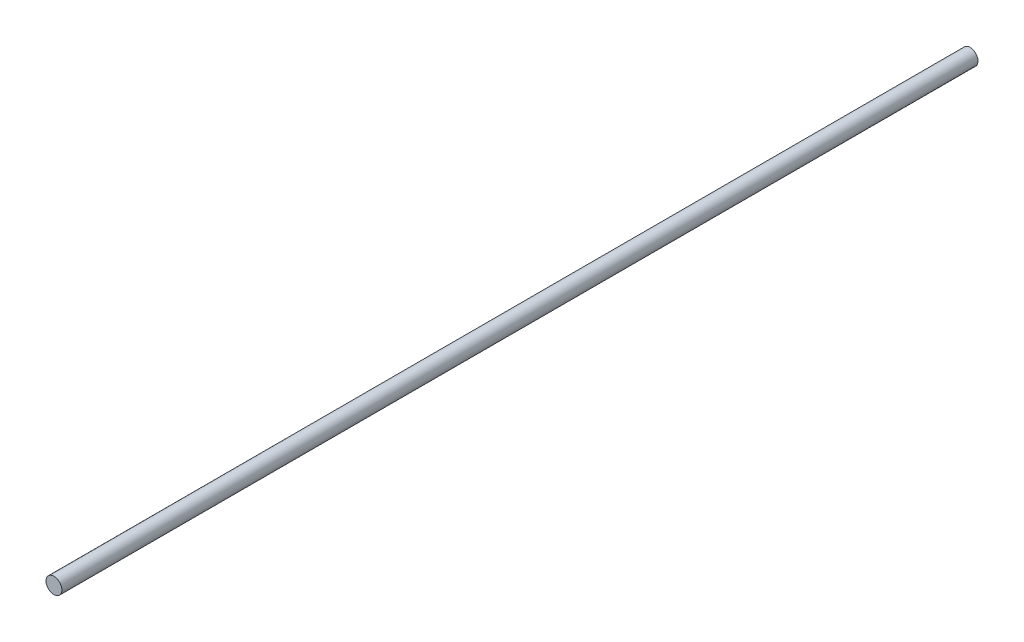
SolidWorks part; units mm, degrees
ref_plane "Спереди" through (0, 0, 0) normal (0, 0, 1) x (1, 0, 0)
ref_plane "Сверху" through (0, 0, 0) normal (0, 1, 0) x (1, 0, 0)
ref_plane "Справа" through (0, 0, 0) normal (1, 0, 0) x (0, 0, -1)
sketch "Эскиз1" plane through (0, 0, 0) normal (0, 0, 1) x (1, 0, 0)
  circle A0 centre (0, 0) radius 6
  dimension "D1" = 12
extrude "Бобышка-Вытянуть1" add sketch "Эскиз1" along normal blind 693
